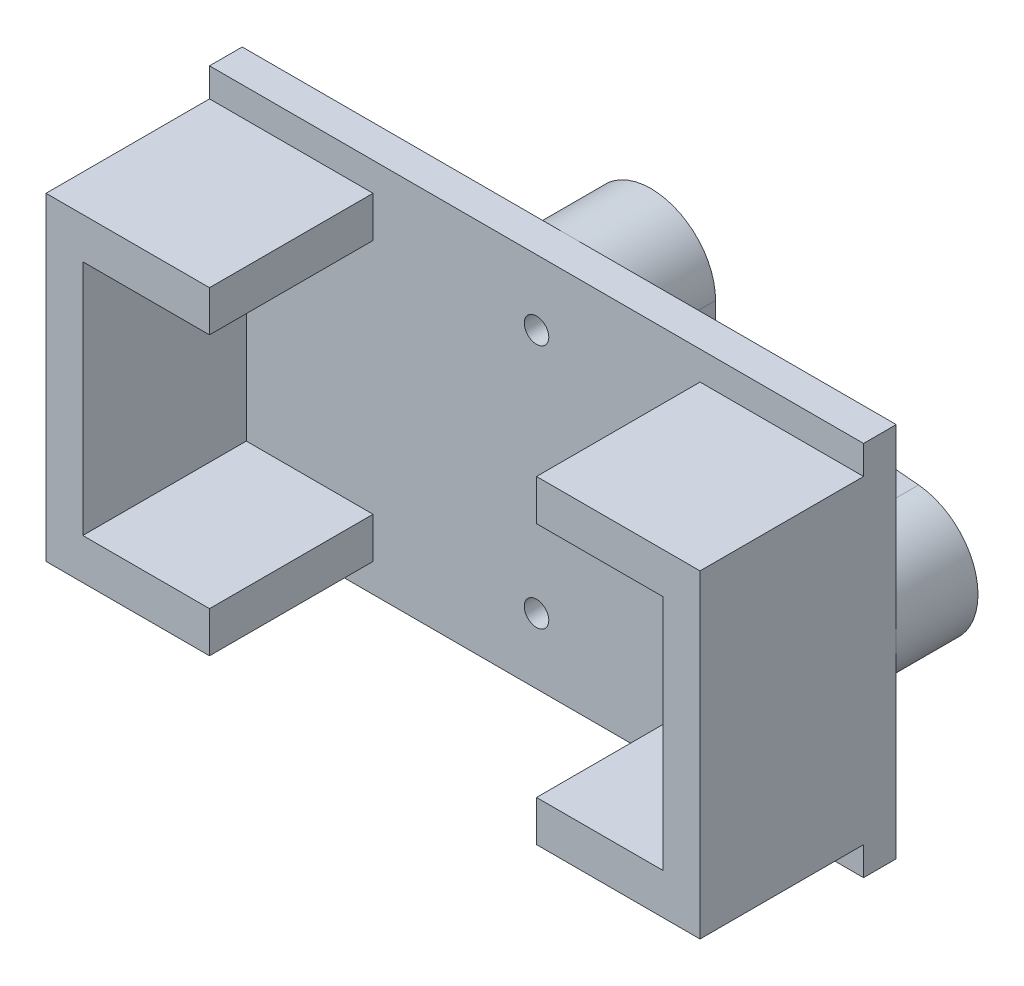
SolidWorks part; units mm, degrees
ref_plane "Alzado" through (0, 0, 0) normal (0, 0, 1) x (1, 0, 0)
ref_plane "Planta" through (0, 0, 0) normal (0, 1, 0) x (1, 0, 0)
ref_plane "Vista lateral" through (0, 0, 0) normal (1, 0, 0) x (0, 0, -1)
sketch "Croquis1" plane through (0, 0, 0) normal (0, 0, 1) x (1, 0, 0)
  line L0 (-2.45, 3.75) -> (-16.2278, 2.4896)
  line L1 (-2.45, 3.75) -> (-2.45, 7.55)
  line L2 (-2.45, -3.75) -> (-2.45, -7.55)
  line L3 (-2.45, -3.75) -> (-16.2278, -2.4896)
  line L4 (2.45, -3.75) -> (2.45, -7.55)
  line L5 (2.45, 3.75) -> (2.45, 7.55)
  line L6 (2.45, 3.75) -> (16.2278, 2.4896)
  line L7 (2.45, -3.75) -> (16.2278, -2.4896)
  line L8 (-3.95, -5.119) -> (-16.3644, -3.9834)
  line L9 (-3.95, 5.119) -> (-16.3644, 3.9834)
  line L10 (-3.95, 5.119) -> (-3.95, 7.55)
  line L11 (3.95, 5.119) -> (3.95, 7.55)
  line L12 (3.95, 5.119) -> (16.3644, 3.9834)
  line L13 (3.95, -5.119) -> (16.3644, -3.9834)
  line L14 (3.95, -5.119) -> (3.95, -7.55)
  line L15 (-3.95, -5.119) -> (-3.95, -7.55)
  line L16 (16, 0) -> (-16, 0) construction
  arc A0 (-16.2278, 2.4896) -> (-16.2278, -2.4896) centre (-16, 0) ccw
  arc A1 (-2.45, 7.55) -> (2.45, 7.55) centre (0, 7.55) cw
  arc A2 (-2.45, -7.55) -> (2.45, -7.55) centre (0, -7.55) ccw
  arc A3 (16.2278, 2.4896) -> (16.2278, -2.4896) centre (16, 0) cw
  arc A4 (-16.3644, 3.9834) -> (-16.3644, -3.9834) centre (-16, 0) ccw
  arc A5 (-3.95, 7.55) -> (3.95, 7.55) centre (0, 7.55) cw
  arc A6 (16.3644, 3.9834) -> (16.3644, -3.9834) centre (16, 0) cw
  arc A7 (-3.95, -7.55) -> (3.95, -7.55) centre (0, -7.55) ccw
  point P32 (3.95, 6.3345)
  point P33 (0, 0)
  dimension "D2" = 2.5
  dimension "D1" = 4.9
  dimension "D3" = 15.1
  dimension "D4" = 32
  dimension "D5" = 7.5
  dimension "D6" = 1.5
extrude "Saliente-Extruir1" add sketch "Croquis1" along normal blind 5
sketch "Croquis2" plane through (0, 0, 5) normal (0, 0, 1) x (1, 0, 0)
  line L5 (20, -11.5) -> (-20, -11.5)
  line L6 (20, -11.5) -> (20, 11.5)
  line L7 (20, 11.5) -> (-20, 11.5)
  line L8 (-20, -11.5) -> (-20, 11.5)
  line L9 (20, -11.5) -> (-20, 11.5) construction
  line L10 (20, 11.5) -> (-20, -11.5) construction
  arc A2 (16.3644, -3.9834) -> (16.3644, 3.9834) centre (16, 0) ccw construction
  arc A3 (3.95, 7.55) -> (-3.95, 7.55) centre (0, 7.55) ccw construction
  point P0 (0, 0)
  point P14 (-33.7598, 13.0077)
extrude "Saliente-Extruir2" add sketch "Croquis2" along normal blind 2
sketch "Croquis3" plane through (0, 0, 7) normal (0, 0, 1) x (1, 0, 0)
  line L0 (-10, 7.25) -> (-10, 9.75)
  line L1 (-17.75, 7.25) -> (-10, 7.25)
  line L2 (-17.75, 7.25) -> (-17.75, -7.25)
  line L3 (-17.75, -7.25) -> (-10, -7.25)
  line L4 (17.75, 7.25) -> (17.75, -7.25)
  line L5 (-17.75, 7.25) -> (17.75, -7.25) construction
  line L6 (-17.75, -7.25) -> (17.75, 7.25) construction
  line L7 (-10, 9.75) -> (-20, 9.75)
  line L8 (-20, 9.75) -> (-20, -9.75)
  line L9 (-20, -9.75) -> (-10, -9.75)
  line L10 (-10, -9.75) -> (-10, -7.25)
  line L11 (10, 7.25) -> (10, 9.75)
  line L12 (10, 9.75) -> (20, 9.75)
  line L13 (20, 9.75) -> (20, -9.75)
  line L14 (20, -9.75) -> (10, -9.75)
  line L15 (10, -9.75) -> (10, -7.25)
  line L16 (10, 7.25) -> (17.75, 7.25)
  line L17 (10, -7.25) -> (17.75, -7.25)
  point P4 (0, 0)
  point P18 (0, 0)
  point P19 (20, 0)
  dimension "D1" = 35.5
  dimension "D2" = 14.5
  dimension "D3" = 2.25
  dimension "D4" = 2.5
  dimension "D5" = 2.5
  dimension "D6" = 10
  dimension "D7" = 10
  dimension "D8" = 2.25
extrude "Saliente-Extruir3" add sketch "Croquis3" along normal blind 10
sketch "Croquis4" plane through (0, 0, 5) normal (0, 0, -1) x (-1, 0, 0)
  line L0 (0, -7.5) -> (0, 7.5) construction
  circle A0 centre (0, -7.5) radius 0.75
  circle A1 centre (0, 7.5) radius 0.75
  point P4 (0, 0)
  dimension "D1" = 1.5
  dimension "D2" = 15
extrude "Cortar-Extruir1" cut sketch "Croquis4" against normal blind 10
